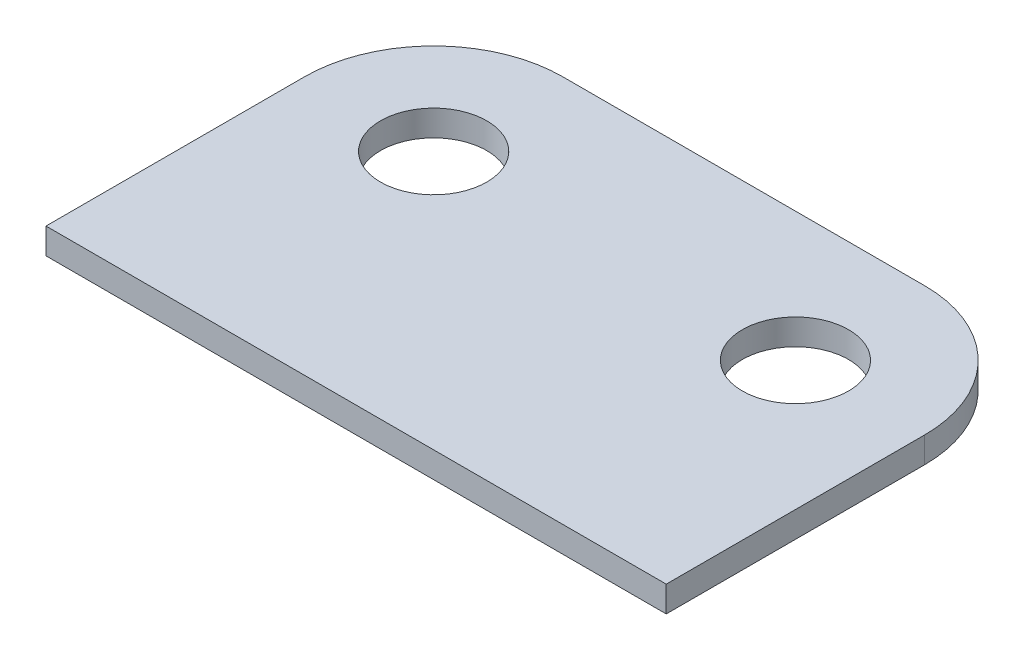
SolidWorks part; units mm, degrees
material "AISI 1020"
ref_plane "Front Plane" through (0, 0, 0) normal (0, 0, 1) x (1, 0, 0)
ref_plane "Top Plane" through (0, 0, 0) normal (0, 1, 0) x (1, 0, 0)
ref_plane "Right Plane" through (0, 0, 0) normal (1, 0, 0) x (0, 0, -1)
sketch "Sketch1" plane through (0, 0, 0) normal (0, 1, 0) x (1, 0, 0)
  line L0 (-19.05, 0) -> (19.05, 0)
  line L1 (19.05, 0) -> (19.05, 15.875)
  line L2 (-19.05, 15.875) -> (-19.05, 0)
  line L3 (-11.1125, 23.8125) -> (11.1125, 23.8125)
  arc A0 (19.05, 15.875) -> (11.1125, 23.8125) centre (11.1125, 15.875) ccw
  arc A2 (-11.1125, 23.8125) -> (-19.05, 15.875) centre (-11.1125, 15.875) ccw
  circle A3 centre (-11.1125, 15.875) radius 3.2639
  circle A4 centre (11.1125, 15.875) radius 3.2639
  point P4 (0, 0)
  dimension "D1" = 6.5278
  dimension "D2" = 38.1
  dimension "D4" = 22.225
  dimension "D3" = 15.875
extrude "Boss-Extrude1" add sketch "Sketch1" along normal blind 1.5875
sketch "Sketch3" plane through (0, 0, 0) normal (0, -1, 0) x (-1, 0, 0)
  line L0 (-11.1125, 23.8125) -> (11.1125, 23.8125) construction
  point P0 (0, 23.8125)
